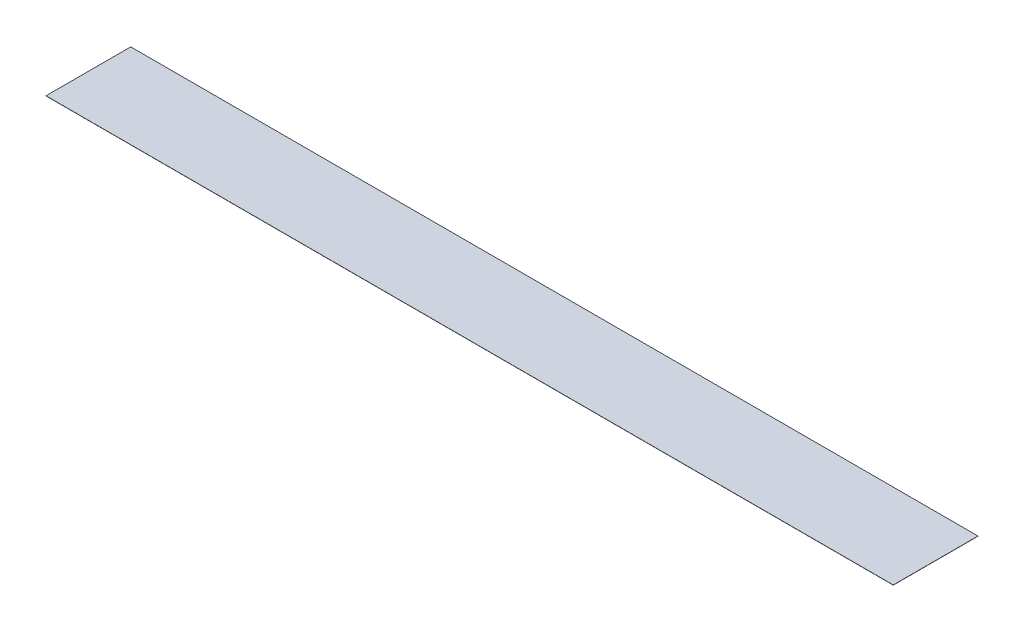
SolidWorks part; units mm, degrees
ref_plane "Front Plane" through (0, 0, 0) normal (0, 0, 1) x (1, 0, 0)
ref_plane "Top Plane" through (0, 0, 0) normal (0, 1, 0) x (1, 0, 0)
ref_plane "Right Plane" through (0, 0, 0) normal (1, 0, 0) x (0, 0, -1)
sketch "Sketch1" plane through (0, 0, 0) normal (0, 1, 0) x (1, 0, 0)
  line L1 (-6350, 635) -> (6350, 635)
  line L2 (-6350, 635) -> (-6350, -635)
  line L3 (-6350, -635) -> (6350, -635)
  line L4 (6350, 635) -> (6350, -635)
  line L5 (-6350, 635) -> (6350, -635) construction
  line L6 (-6350, -635) -> (6350, 635) construction
  point P0 (0, 0)
  dimension "D1" = 1270
  dimension "D2" = 12700
extrude "Boss-Extrude1" add sketch "Sketch1" along normal blind 2.54
